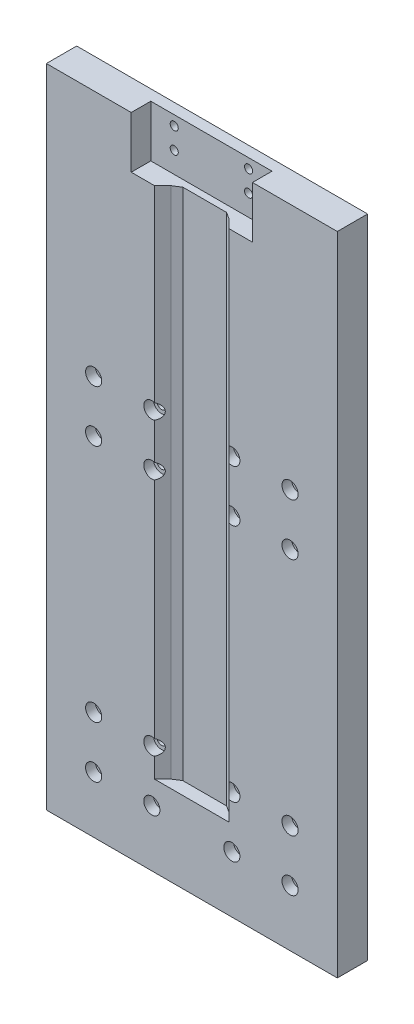
SolidWorks part; units mm, degrees
ref_plane "Front Plane" through (0, 0, 0) normal (0, 0, 1) x (1, 0, 0)
ref_plane "Top Plane" through (0, 0, 0) normal (0, 1, 0) x (1, 0, 0)
ref_plane "Right Plane" through (0, 0, 0) normal (1, 0, 0) x (0, 0, -1)
sketch "Sketch1" plane through (0, 0, 0) normal (0, 0, 1) x (1, 0, 0)
  line L4 (90, 22) -> (90, -210)
  line L5 (-90, -235) -> (-90, 165)
  line L7 (-90, -235) -> (90, -235)
  line L8 (90, -235) -> (90, -210)
  line L9 (-90, 165) -> (90, 165)
  line L10 (90, 165) -> (90, 22)
  point P0 (0, -94)
extrude "Boss-Extrude1" add sketch "Sketch1" along normal blind 18.75
sketch "Sketch2" plane through (0, 0, 0) normal (0, 0, -1) x (-1, 0, 0)
  circle A48 centre (31, -21.11) radius 2.4585 construction
  circle A49 centre (84, -21.11) radius 2.4585 construction
  circle A50 centre (84, -61.11) radius 2.4585 construction
  circle A51 centre (31, -61.11) radius 2.4585 construction
  circle A52 centre (31, -146.37) radius 2.4585 construction
  circle A53 centre (84, -146.37) radius 2.4585 construction
  circle A54 centre (84, -186.37) radius 2.4585 construction
  circle A55 centre (31, -186.37) radius 2.4585 construction
  circle A56 centre (-31, -186.37) radius 2.4585 construction
  circle A57 centre (-84, -186.37) radius 2.4585 construction
  circle A58 centre (-31, -146.37) radius 2.4585 construction
  circle A59 centre (-84, -146.37) radius 2.4585 construction
  circle A60 centre (-31, -61.11) radius 2.4585 construction
  circle A61 centre (-84, -61.11) radius 2.4585 construction
  circle A62 centre (-31, -21.11) radius 2.4585 construction
  circle A63 centre (-84, -21.11) radius 2.4585 construction
  circle A64 centre (31, -21.11) radius 2.4585
  circle A65 centre (84, -21.11) radius 2.4585
  circle A66 centre (84, -61.11) radius 2.4585
  circle A67 centre (31, -61.11) radius 2.4585
  circle A68 centre (31, -146.37) radius 2.4585
  circle A69 centre (84, -146.37) radius 2.4585
  circle A70 centre (84, -186.37) radius 2.4585
  circle A71 centre (31, -186.37) radius 2.4585
  circle A72 centre (-31, -186.37) radius 2.4585
  circle A73 centre (-84, -186.37) radius 2.4585
  circle A74 centre (-31, -146.37) radius 2.4585
  circle A75 centre (-84, -146.37) radius 2.4585
  circle A76 centre (-31, -61.11) radius 2.4585
  circle A77 centre (-84, -61.11) radius 2.4585
  circle A78 centre (-31, -21.11) radius 2.4585
  circle A79 centre (-84, -21.11) radius 2.4585
sketch "Sketch5" plane through (0, 0, 18.75) normal (0, 0, 1) x (1, 0, 0)
  circle A16 centre (24.75, -168) radius 2.1
  circle A17 centre (60.75, -168) radius 2.1
  circle A18 centre (60.75, -200) radius 2.1
  circle A19 centre (24.75, -200) radius 2.1
  circle A20 centre (-24.75, -200) radius 2.1
  circle A21 centre (-60.75, -200) radius 2.1
  circle A22 centre (-60.75, -168) radius 2.1
  circle A23 centre (-24.75, -168) radius 2.1
  circle A24 centre (-24.75, -20) radius 2.1
  circle A25 centre (-60.75, -20) radius 2.1
  circle A26 centre (-24.75, 12) radius 2.1
  circle A27 centre (-60.75, 12) radius 2.1
  circle A28 centre (60.75, -20) radius 2.1
  circle A29 centre (24.75, -20) radius 2.1
  circle A30 centre (24.75, 12) radius 2.1
  circle A31 centre (60.75, 12) radius 2.1
hole_wizard "CBORE for M5 SHCS2" positions "Sketch26" profile "Sketch27" counterbore size "M5" standard "ANSI Metric" end condition through all
sketch "Sketch26" plane through (0, 0, 18.75) normal (0, 0, 1) x (1, 0, 0)
  point P0 (-60.75, -200)
  point P3 (-60.75, -168)
  point P6 (-24.75, -168)
  point P9 (-24.75, -200)
  point P12 (24.75, -200)
  point P15 (24.75, -168)
  point P18 (60.75, -168)
  point P21 (60.75, -200)
  point P24 (-60.75, -20)
  point P27 (-60.75, 12)
  point P33 (-24.75, -20)
  point P36 (24.75, 12)
  point P39 (60.75, 12)
  point P42 (60.75, -20)
  point P45 (24.75, -20)
  point P50 (-24.75, 12)
sketch "Sketch27" plane through (-60.75, -200, 18.75) normal (1, 0, 0) x (0, -1, 0)
  line L0 (0, 0) -> (0, 18.75)
  line L1 (0, 18.75) -> (2.75, 18.75)
  line L3 (2.75, 18.75) -> (2.75, 6)
  line L4 (2.75, 6) -> (5, 6)
  line L5 (5, 6) -> (5, 0)
  line L7 (5, 0) -> (0, 0)
  line L11 (0, -6.35) -> (0, 107.95) construction
  dimension "Thru Hole Dia." = 5.5
  dimension "Thru Hole Depth" = 18.75
  dimension "C'Bore Dia." = 10
  dimension "C'Bore Depth" = 6
sketch "Sketch11" plane through (0, 0, 0) normal (0, 0, 1) x (1, 0, 0)
  circle A4 centre (-20, -94) radius 4.3
  circle A5 centre (-20, -118) radius 4.3
  circle A6 centre (20, -118) radius 4.3
  circle A7 centre (20, -94) radius 4.3
sketch "Sketch28" plane through (0, 165, 0) normal (0, 1, 0) x (1, 0, 0)
  line L10 (23.075, -18.75) -> (17.9469, -13.622)
  line L11 (13.5558, -10.7963) -> (17.9469, -13.622)
  line L12 (13.5558, -10.7963) -> (-13.5558, -10.7963)
  line L13 (-17.9469, -13.622) -> (-13.5558, -10.7963)
  line L14 (-17.9469, -13.622) -> (-23.075, -18.75)
  line L15 (90, -18.75) -> (-90, -18.75) construction
  line L16 (23.075, -18.75) -> (-23.075, -18.75)
  point P0 (26, -23.7963)
  point P5 (17, -14.7963)
  point P8 (-17, -14.7963)
  point P9 (-26, -23.7963)
  point P11 (-27.0607, -22.7357)
extrude "Cut-Extrude1" cut sketch "Sketch28" against normal blind 350
sketch "Sketch29" plane through (0, 0, 18.75) normal (0, 0, 1) x (1, 0, 0)
  line L2 (0, 165) -> (37.5, 165)
  line L3 (0, 165) -> (-37.5, 165)
  line L4 (37.5, 165) -> (37.5, 133)
  line L5 (37.5, 133) -> (-37.5, 133)
  line L6 (-37.5, 133) -> (-37.5, 165)
extrude "Cut-Extrude2" cut sketch "Sketch29" against normal blind 12.1
sketch "Sketch30" plane through (0, 0, 6.65) normal (0, 0, 1) x (1, 0, 0)
  circle A0 centre (23, 159) radius 2.5
  circle A1 centre (-23, 159) radius 2.5
  circle A2 centre (23, 146) radius 2.5
  circle A3 centre (-23, 146) radius 2.5
extrude "Cut-Extrude3" cut sketch "Sketch30" against normal through all
